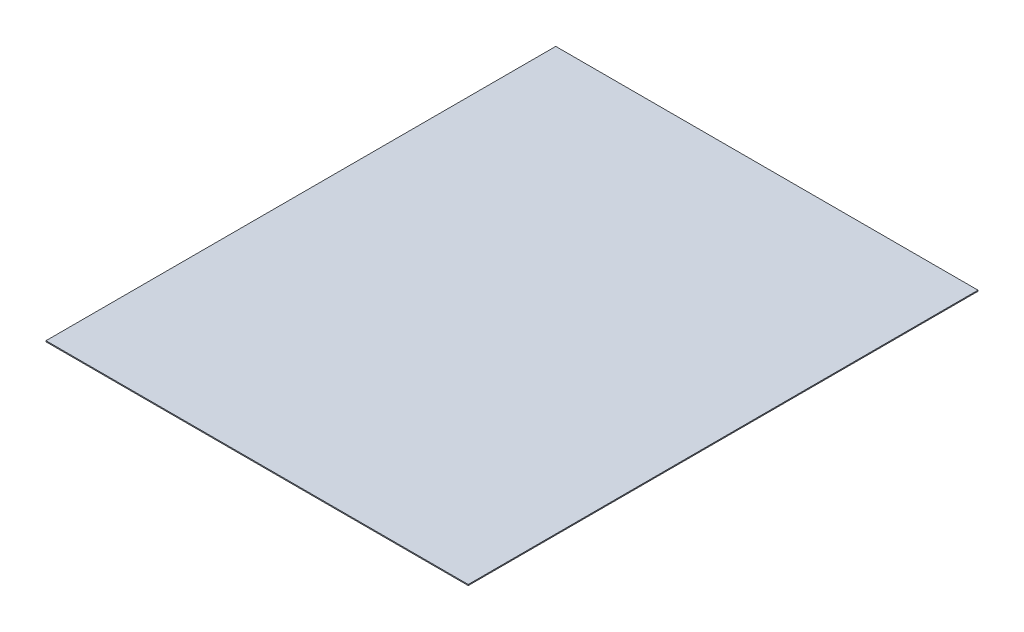
SolidWorks part; units mm, degrees
ref_plane "Front Plane" through (0, 0, 0) normal (0, 0, 1) x (1, 0, 0)
ref_plane "Top Plane" through (0, 0, 0) normal (0, 1, 0) x (1, 0, 0)
ref_plane "Right Plane" through (0, 0, 0) normal (1, 0, 0) x (0, 0, -1)
other "Configuration Table"
sketch "Sketch1" plane through (0, 0, 0) normal (0, 0, 1) x (1, 0, 0)
  line L1 (62.5, 403) -> (690, 403)
  line L2 (62.5, 403) -> (62.5, 404.5)
  line L3 (62.5, 404.5) -> (690, 404.5)
  line L4 (690, 403) -> (690, 404.5)
extrude "STORE_klape_kaset_kati_raf_1" add sketch "Sketch1" against normal blind 757.5 separate body
